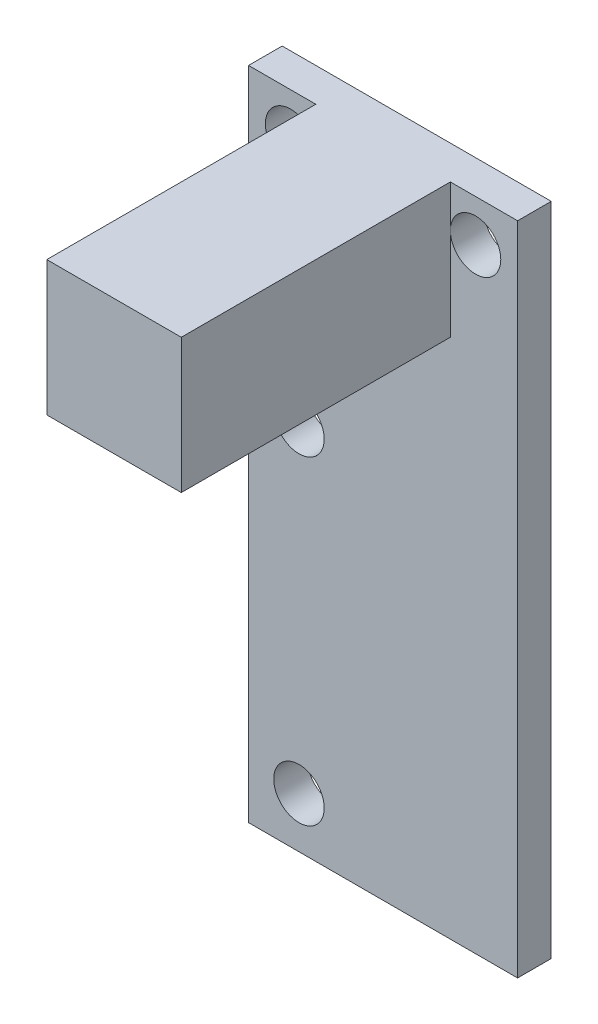
SolidWorks part; units mm, degrees
ref_plane "Front Plane" through (0, 0, 0) normal (0, 0, 1) x (1, 0, 0)
ref_plane "Top Plane" through (0, 0, 0) normal (0, 1, 0) x (1, 0, 0)
ref_plane "Right Plane" through (0, 0, 0) normal (1, 0, 0) x (0, 0, -1)
ref_plane "Plane1" through (0, 0, 2) normal (0, 0, 1) x (1, 0, 0)
sketch "Sketch1" plane through (0, 0, 2) normal (0, 0, 1) x (1, 0, 0)
  line L0 (16, 39) -> (0, 39)
  line L1 (0, 39) -> (0, 0)
  line L2 (0, 0) -> (16, 0)
  line L3 (16, 0) -> (16, 39)
extrude "Boss-Extrude1" add sketch "Sketch1" against normal blind 2
sketch "Sketch2" plane through (0, 0, 2) normal (0, 0, 1) x (1, 0, 0)
  line L0 (4, 31) -> (4, 39)
  line L1 (4, 39) -> (12, 39)
  line L2 (12, 39) -> (12, 31)
  line L3 (12, 31) -> (4, 31)
extrude "Boss-Extrude2" add sketch "Sketch2" along normal blind 16
hole_wizard "Hole1" positions "Sketch4" profile "Sketch3" legacy
sketch "Sketch4" plane through (0, 0, 2) normal (0, 0, 1) x (1, 0, 0)
  point P0 (3, 3)
sketch "Sketch3" plane through (3, 3, 2) normal (1, 0, 0) x (0, -1, 0)
  line L0 (0, 0) -> (0, 2)
  line L1 (0, 2) -> (1.5, 2)
  line L2 (1.5, 2) -> (1.5, 0)
  line L3 (1.5, 0) -> (0, 0)
  line L4 (0, 110) -> (0, -10) construction
  dimension "Diameter" = 3
  dimension "Depth" = 2
hole_wizard "Hole2" positions "Sketch6" profile "Sketch5" legacy
sketch "Sketch6" plane through (0, 0, 2) normal (0, 0, 1) x (1, 0, 0)
  point P0 (13.5, 36.5)
sketch "Sketch5" plane through (13.5, 36.5, 2) normal (1, 0, 0) x (0, -1, 0)
  line L0 (0, 0) -> (0, 2)
  line L1 (0, 2) -> (1.5, 2)
  line L2 (1.5, 2) -> (1.5, 0)
  line L3 (1.5, 0) -> (0, 0)
  line L4 (0, 110) -> (0, -10) construction
  dimension "Diameter" = 3
  dimension "Depth" = 2
hole_wizard "Hole3" positions "Sketch8" profile "Sketch7" legacy
sketch "Sketch8" plane through (0, 0, 2) normal (0, 0, 1) x (1, 0, 0)
  point P0 (2.5, 36.5)
sketch "Sketch7" plane through (2.5, 36.5, 2) normal (1, 0, 0) x (0, -1, 0)
  line L0 (0, 0) -> (0, 2)
  line L1 (0, 2) -> (1.5, 2)
  line L2 (1.5, 2) -> (1.5, 0)
  line L3 (1.5, 0) -> (0, 0)
  line L4 (0, 110) -> (0, -10) construction
  dimension "Diameter" = 3
  dimension "Depth" = 2
hole_wizard "Hole4" positions "Sketch10" profile "Sketch9" legacy
sketch "Sketch10" plane through (0, 0, 2) normal (0, 0, 1) x (1, 0, 0)
  point P0 (3, 22)
sketch "Sketch9" plane through (3, 22, 2) normal (1, 0, 0) x (0, -1, 0)
  line L0 (0, 0) -> (0, 2)
  line L1 (0, 2) -> (1.5, 2)
  line L2 (1.5, 2) -> (1.5, 0)
  line L3 (1.5, 0) -> (0, 0)
  line L4 (0, 110) -> (0, -10) construction
  dimension "Diameter" = 3
  dimension "Depth" = 2
